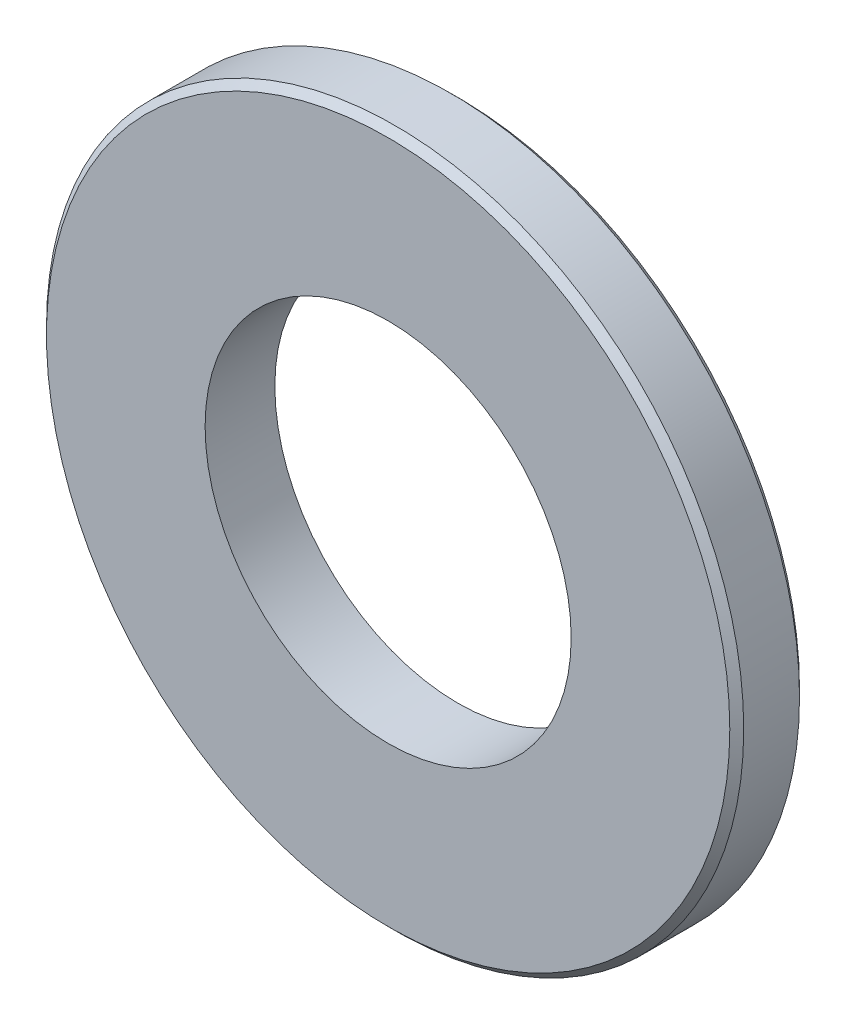
SolidWorks part; units mm, degrees
material "Alloy Steel"
ref_plane "Front Plane" through (0, 0, 0) normal (0, 0, 1) x (1, 0, 0)
ref_plane "Top Plane" through (0, 0, 0) normal (0, 1, 0) x (1, 0, 0)
ref_plane "Right Plane" through (0, 0, 0) normal (1, 0, 0) x (0, 0, -1)
sketch "Sketch1" plane through (0, 0, 0) normal (0, 0, 1) x (1, 0, 0)
  circle A0 centre (0, 0) radius 10
  circle A1 centre (0, 0) radius 5.25
  dimension "D1" = 20
  dimension "D2" = 10.5
extrude "Boss-Extrude1" add sketch "Sketch1" along normal blind 2
chamfer "Chamfer1" distance 0.2 angle 45 2 edges at (10, 0, 0) (10, 0, 2)
